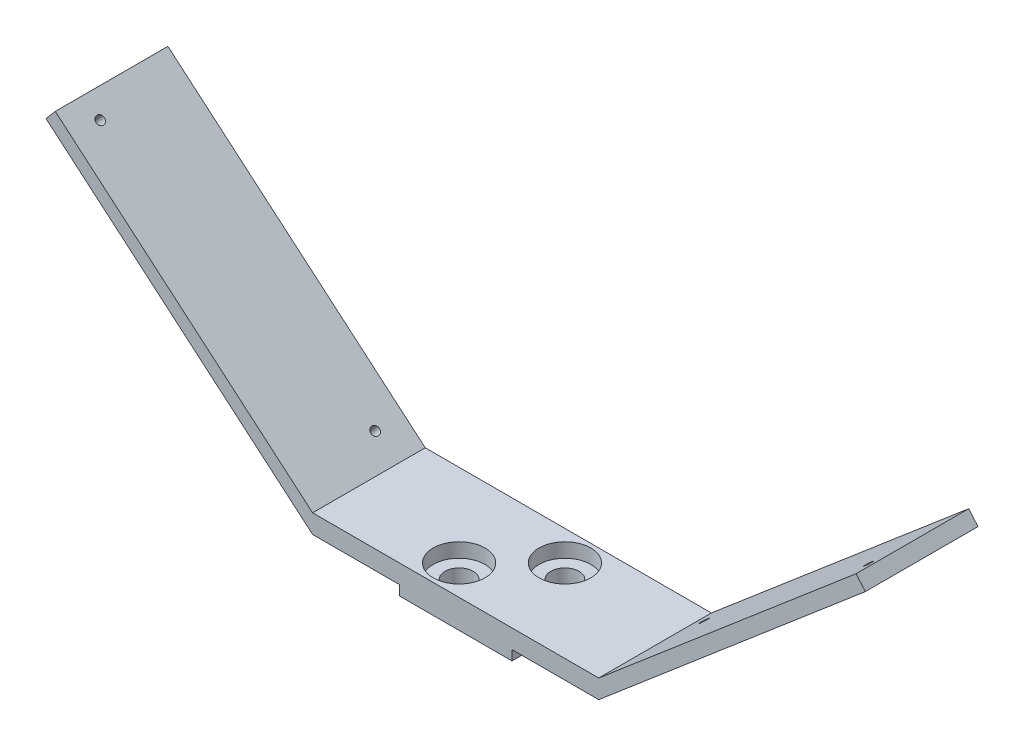
SolidWorks part; units mm, degrees
ref_plane "Front Plane" through (0, 0, 0) normal (0, 0, 1) x (1, 0, 0)
ref_plane "Top Plane" through (0, 0, 0) normal (0, 1, 0) x (1, 0, 0)
ref_plane "Right Plane" through (0, 0, 0) normal (1, 0, 0) x (0, 0, -1)
sketch "Sketch1" plane through (0, 0, 0) normal (0, 1, 0) x (1, 0, 0)
  line L1 (10, -10) -> (-10, -10)
  line L2 (10, -10) -> (10, 10)
  line L3 (10, 10) -> (-10, 10)
  line L4 (-10, -10) -> (-10, 10)
  line L5 (10, -10) -> (-10, 10) construction
  line L6 (10, 10) -> (-10, -10) construction
  circle A0 centre (-4.6967, 4.6967) radius 2.5 construction
  circle A1 centre (4.6967, -4.6967) radius 2.5 construction
  circle A2 centre (4.6967, 4.6967) radius 2.5
  circle A3 centre (-4.6967, -4.6967) radius 2.5
  point P0 (0, 0)
  point P10 (0, 0)
  dimension "D3" = 5
  dimension "D1" = 20
  dimension "D2" = 20
  dimension "D4" = 7.5
extrude "Boss-Extrude1" add sketch "Sketch1" along normal blind 2.54
sketch "Sketch2" plane through (0, 2.54, 0) normal (0, 1, 0) x (1, 0, 0)
  line L1 (25.4, -10) -> (-25.4, -10)
  line L2 (25.4, -10) -> (25.4, 10)
  line L3 (25.4, 10) -> (-25.4, 10)
  line L4 (-25.4, -10) -> (-25.4, 10)
  line L5 (25.4, -10) -> (-25.4, 10) construction
  line L6 (25.4, 10) -> (-25.4, -10) construction
  circle A2 centre (-4.6967, -4.6967) radius 2.5 construction
  circle A3 centre (4.6967, 4.6967) radius 2.5 construction
  circle A4 centre (4.6967, 4.6967) radius 4.6
  circle A5 centre (-4.6967, -4.6967) radius 4.6
  circle A6 centre (4.6967, 4.6967) radius 2.5 construction
  circle A7 centre (4.6967, 4.6967) radius 2.5
  circle A8 centre (-4.6967, -4.6967) radius 2.5 construction
  circle A9 centre (-4.6967, -4.6967) radius 2.5
  point P0 (0, 0)
  point P6 (-1.5746, 5.2059)
  point P16 (0, 0)
  point P20 (0, 0)
  line M4 (-10, 10) -> (-10, -10)
  line M5 (-10, -10) -> (10, -10)
  line M6 (10, -10) -> (10, 10)
  line M7 (10, 10) -> (-10, 10)
  dimension "D2" = 9.2
  dimension "D1" = 50.8
  dimension "D3" = 20
extrude "Boss-Extrude2" add sketch "Sketch2" along normal blind 2.54 contours L4 L1 L3 M4 | A5 A4 M7 M4 M5 M6 | L2 L3 L1 M6
sketch "Sketch3" plane through (0, 0, 10) normal (0, 0, 1) x (1, 0, 0)
  line L0 (0, -1000) -> (0, 49000) construction
  line L1 (-10, 0) -> (10, 0) construction
  line L2 (-25.4, 5.08) -> (-71.0947, 43.9643)
  line L3 (-60.8134, 35.2153) -> (0, 106.68) construction
  line L4 (-71.0947, 43.9643) -> (-72.7408, 42.0299)
  line L5 (-72.7408, 42.0299) -> (-25.4, 1.7448)
  line L6 (-25.4, 1.7448) -> (-10, 1.7448)
  line L7 (-10, 2.54) -> (-10, 0) construction
  line L8 (25.4, 1.7448) -> (10, 1.7448)
  line L9 (72.7408, 42.0299) -> (25.4, 1.7448)
  line L10 (71.0947, 43.9643) -> (72.7408, 42.0299)
  line L11 (25.4, 5.08) -> (71.0947, 43.9643)
  line L12 (60.8134, 35.2153) -> (0, 106.68) construction
  line L14 (25.4, 5.08) -> (-25.4, 5.08) construction
  line L15 (25.4, 5.08) -> (-25.4, 5.08)
  point P5 (0, 0)
  point P10 (0, 0)
  dimension "D1" = 60
  dimension "D2" = 106.68
  dimension "D3" = 2.54
  dimension "D4" = 46.5
extrude "Boss-Extrude3" add sketch "Sketch3" against normal up to surface (20 mm away) up to face at (0, 2.54, -10)
sketch "Sketch4" plane through (-8.1607, -9.59, 0) normal (0.6481, 0.7616, 0) x (0.7616, -0.6481, 0)
  line L0 (-22.6363, 0) -> (-82.6363, 0) construction
  line L1 (-82.6363, 10) -> (-82.6363, -10)
  line L2 (-82.6363, 10) -> (-82.6363, -10) construction
  line L3 (-22.6363, 4.9) -> (-26.4363, 4.9)
  line L4 (-22.6363, 0) -> (-22.6363, -4.9)
  line L5 (-22.6363, -4.9) -> (-77.6363, -4.9)
  line L6 (-52.6363, 10) -> (-52.6363, -10) construction
  line L7 (-82.6363, 10) -> (-22.6363, 10) construction
  line L8 (-22.6363, -10) -> (-82.6363, -10) construction
  line L9 (-22.6363, -10) -> (-22.6363, 10) construction
  line L10 (-22.6363, -10) -> (-22.6363, 10)
  circle A0 centre (-26.4363, 4.9) radius 0.75 construction
  circle A1 centre (-77.6363, -4.9) radius 0.75 construction
  circle A2 centre (-27.6363, -4.9) radius 0.75 construction
  circle A3 centre (-78.8363, 4.9) radius 0.75 construction
  circle A4 centre (-27.6363, 4.9) radius 0.75
  circle A5 centre (-78.8363, -4.9) radius 0.75
  point P26 (0, 0)
  point P27 (0, 0)
  point P28 (0, 0)
  point P29 (0, 0)
  point P30 (0, 0)
  dimension "D3" = 1.5
  dimension "D1" = 3.8
  dimension "D2" = 4.9
  dimension "D4" = 4.9
  dimension "D5" = 55
extrude "Cut-Extrude1" cut sketch "Sketch4" against normal up to surface (257.1035 mm away)
mirror "Mirror1" about plane through (0, 0, 0) normal (1, 0, 0) of "Cut-Extrude1"
